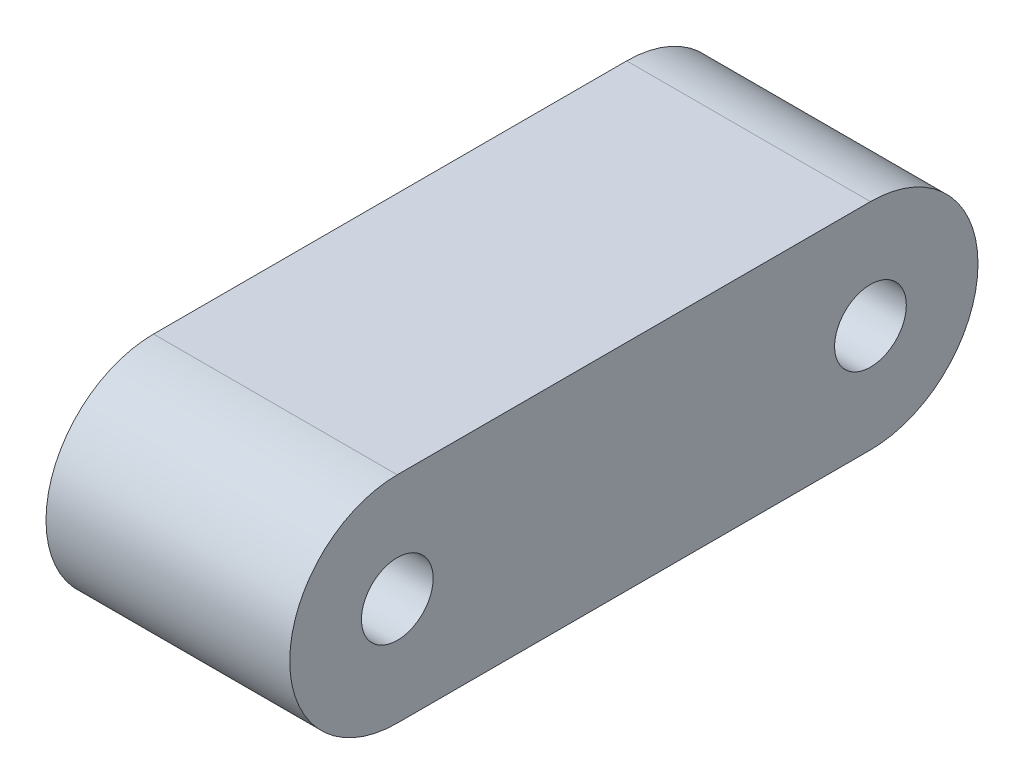
SolidWorks part; units mm, degrees
ref_plane "Alzado" through (0, 0, 0) normal (0, 0, 1) x (1, 0, 0)
ref_plane "Planta" through (0, 0, 0) normal (0, 1, 0) x (1, 0, 0)
ref_plane "Vista lateral" through (0, 0, 0) normal (1, 0, 0) x (0, 0, -1)
sketch "Croquis1" plane through (0, 0, 0) normal (1, 0, 0) x (0, 0, -1)
  line L0 (-16.5, 0) -> (16.5, 0) construction
  line L1 (-16.5, 7.5) -> (16.5, 7.5)
  line L2 (-16.5, -7.5) -> (16.5, -7.5)
  circle A0 centre (-16.5, 0) radius 2.5
  circle A1 centre (16.5, 0) radius 2.5
  arc A2 (-16.5, 7.5) -> (-16.5, -7.5) centre (-16.5, 0) ccw
  arc A3 (16.5, -7.5) -> (16.5, 7.5) centre (16.5, 0) ccw
  point P3 (0, 0)
  dimension "D1" = 5
  dimension "D3" = 15
  dimension "D2" = 33
extrude "Saliente-Extruir1" add sketch "Croquis1" along normal mid plane 17
